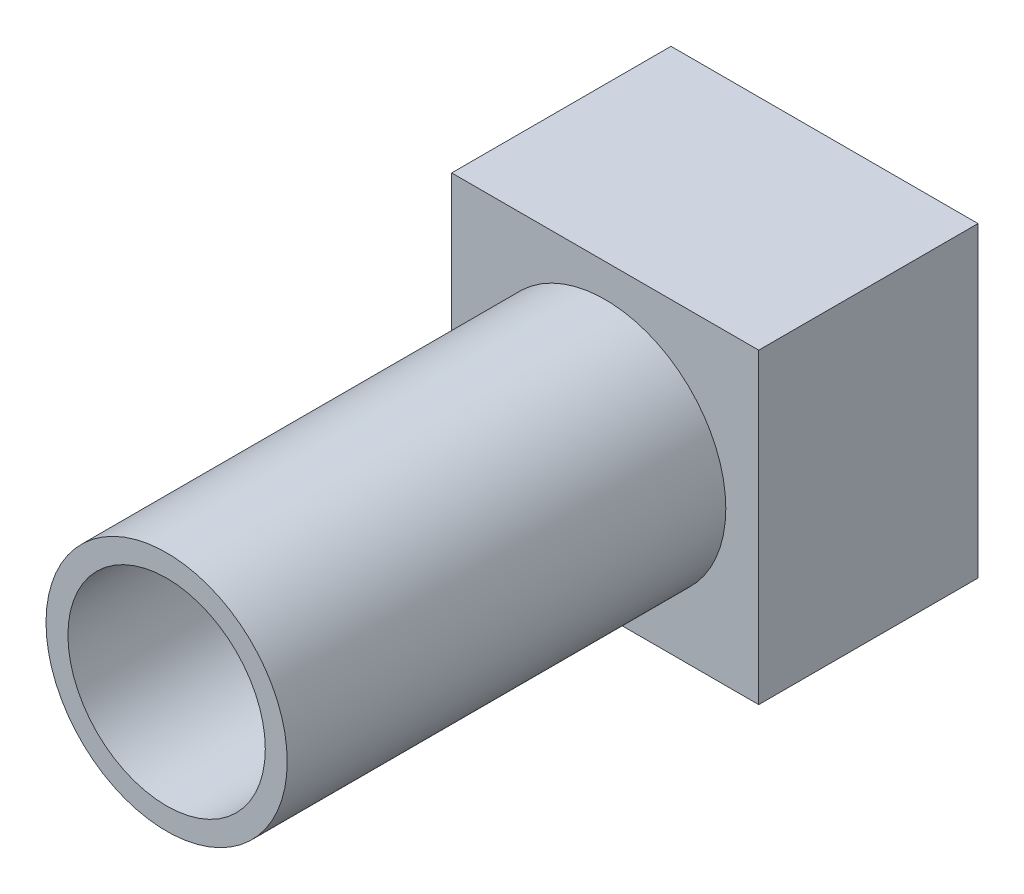
SolidWorks part; units mm, degrees
ref_plane "前视基准面" through (0, 0, 0) normal (0, 0, 1) x (1, 0, 0)
ref_plane "上视基准面" through (0, 0, 0) normal (0, 1, 0) x (1, 0, 0)
ref_plane "右视基准面" through (0, 0, 0) normal (1, 0, 0) x (0, 0, -1)
sketch "草图1" plane through (0, 0, 0) normal (0, 0, 1) x (1, 0, 0)
  line L1 (-5.5, -5.5) -> (5.5, -5.5)
  line L2 (-5.5, -5.5) -> (-5.5, 5.5)
  line L3 (-5.5, 5.5) -> (5.5, 5.5)
  line L4 (5.5, -5.5) -> (5.5, 5.5)
  line L5 (-5.5, -5.5) -> (5.5, 5.5) construction
  line L6 (-5.5, 5.5) -> (5.5, -5.5) construction
  line L7 (-7, -7) -> (7, -7)
  line L8 (-7, -7) -> (-7, 7)
  line L9 (-7, 7) -> (7, 7)
  line L10 (7, -7) -> (7, 7)
  line L11 (-7, -7) -> (7, 7) construction
  line L12 (-7, 7) -> (7, -7) construction
  point P0 (0, 0)
  point P6 (0, 0)
  dimension "D1" = 14
  dimension "D2" = 14
  dimension "D3" = 11
  dimension "D4" = 11
extrude "凸台-拉伸1" add sketch "草图1" along normal blind 5 contours L7 L10 L9 L8 L4 L1 L2 L3
sketch "草图2" plane through (0, 0, 5) normal (0, 0, 1) x (1, 0, 0)
  line L1 (-7, -7) -> (7, -7)
  line L2 (-7, -7) -> (-7, 7)
  line L3 (-7, 7) -> (7, 7)
  line L4 (7, -7) -> (7, 7)
  line L5 (-7, -7) -> (7, 7) construction
  line L6 (-7, 7) -> (7, -7) construction
  point P0 (0, 0)
extrude "凸台-拉伸2" add sketch "草图2" along normal blind 5
sketch "草图3" plane through (0, 0, 10) normal (0, 0, 1) x (1, 0, 0)
  circle A0 centre (0, 0) radius 5.5
  dimension "D1" = 11
extrude "凸台-拉伸3" add sketch "草图3" along normal blind 20
sketch "草图4" plane through (0, 0, 30) normal (0, 0, 1) x (1, 0, 0)
  circle A0 centre (0, 0) radius 4.5
  dimension "D1" = 9
extrude "切除-拉伸1" cut sketch "草图4" against normal through all contours A0
